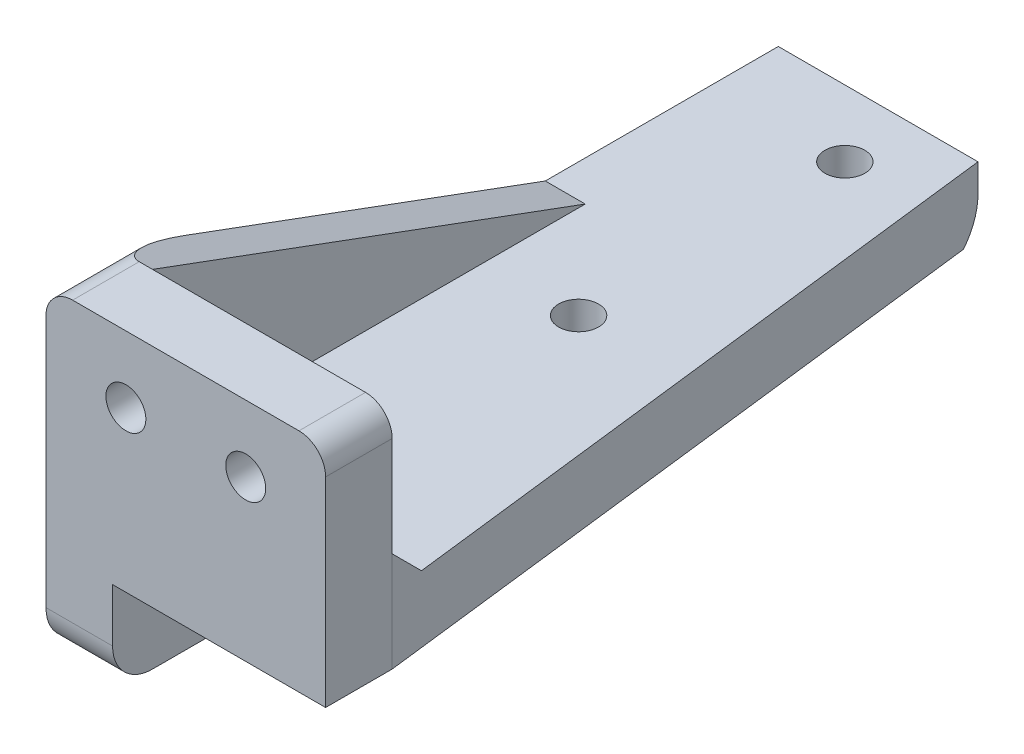
SolidWorks part; units mm, degrees
material "聚脂树脂"
ref_plane "前视基准面" through (0, 0, 0) normal (0, 0, 1) x (1, 0, 0)
ref_plane "上视基准面" through (0, 0, 0) normal (0, 1, 0) x (1, 0, 0)
ref_plane "右视基准面" through (0, 0, 0) normal (1, 0, 0) x (0, 0, -1)
other "Configuration Table"
sketch "草图1" plane through (0, 0, 0) normal (0, 1, 0) x (1, 0, 0)
  line L0 (7.5, -25) -> (13.5, -25)
  line L1 (-7.5, -25) -> (7.5, -25)
  line L2 (-7.5, -25) -> (-7.5, 25)
  line L3 (-7.5, 25) -> (7.5, 25)
  line L4 (7.5, -25) -> (7.5, 25)
  line L5 (-7.5, -25) -> (7.5, 25) construction
  line L6 (-7.5, 25) -> (7.5, -25) construction
  line L7 (13.5, -25) -> (7.5, 25)
  point P0 (0, 0)
  dimension "D1" = 15
  dimension "D2" = 6
  dimension "D3" = 50
extrude "凸台-拉伸1" add sketch "草图1" along normal blind 5 contours L1 L4 L3 L2 | L0 L7 L4
sketch "草图3" plane through (-7.5, 0, 0) normal (-1, 0, 0) x (0, 0, 1)
  line L0 (-25, 0) -> (25, 0)
  line L1 (25, 0) -> (25, -1)
  line L2 (25, -1) -> (-25, -1)
  line L3 (-25, -1) -> (-25, 0)
  line L4 (-25, -1) -> (15, -2)
  line L5 (15, -2) -> (25, -2)
  line L6 (25, -2) -> (25, -1)
  line L7 (25, -2) -> (25, -7)
  line L8 (25, -7) -> (15, -7)
  line L9 (15, -7) -> (15, -2)
  line M10 (-25, 0) -> (25, 0)
  dimension "D1" = 1
  dimension "D2" = 1
  dimension "D3" = 10
  dimension "D4" = 5
  dimension "D5" = 5
extrude "凸台-拉伸2" add sketch "草图3" against normal blind 5 contours L3 L2 L1 M10 | L5 L6 L2 L4 | L9 L8 L7 L5
fillet "圆角1" radius 4 1 edges at (-5, -1, -25)
fillet "圆角2" radius 2 1 edges at (-5, -7, 15)
sketch "草图4" plane through (0, 0, 0) normal (0, -1, 0) x (1, 0, 0)
  line L0 (-2.5, -23.7537) -> (-2.5, 25) construction
  line L1 (-2.5, -21.1) -> (-2.5, 15) construction
  line L2 (-2.5, -25) -> (7.5, -25) construction
  circle A0 centre (2.5, 20) radius 1.5
  circle A1 centre (2.5, 0) radius 1.5
  circle A2 centre (2.5, -20) radius 1.5
  dimension "D1" = 3
  dimension "D2" = 3
  dimension "D3" = 3
  dimension "D4" = 5
  dimension "D5" = 5
  dimension "D6" = 5
  dimension "D7" = 20
  dimension "D8" = 20
  dimension "D9" = 5
extrude "切除-拉伸1" cut sketch "草图4" against normal blind 5
sketch "草图5" plane through (0, 0, 25) normal (0, 0, 1) x (1, 0, 0)
  line L0 (13.5, 5) -> (13.5, 0)
  line L1 (-2.5, 0) -> (13.5, 0) construction
  line L2 (13.5, 5) -> (13.5, 0) construction
  line L3 (13.5, 0) -> (-2.5, 0)
  line L4 (-2.5, 0) -> (-2.5, -7)
  line L5 (-2.5, -7) -> (-7.5, -7)
  line L6 (-7.5, -7) -> (-7.5, 5)
  line L7 (-7.5, 5) -> (-7.5, 17)
  line L8 (-7.5, 17) -> (13.5, 17)
  line L9 (13.5, 17) -> (13.5, 5)
  circle A0 centre (-1.5, 12) radius 1.5
  circle A1 centre (7.5, 12) radius 1.5
  dimension "D2" = 3
  dimension "D3" = 3
  dimension "D1" = 12
  dimension "D4" = 5
  dimension "D5" = 6
  dimension "D6" = 6
  dimension "D7" = 5
extrude "凸台-拉伸3" add sketch "草图5" along normal blind 5
chamfer "倒角1" distance 2.5 angle 45 1 edges at (3, 5, 25)
fillet "圆角4" radius 3 1 edges at (-5, -7, 30)
sketch "草图6" plane through (-7.5, 0, 0) normal (-1, 0, 0) x (0, 0, 1)
  line L0 (25, 17) -> (25, 7.5)
  line L1 (25, 7.5) -> (22.5, 5)
  line L2 (22.5, 5) -> (-7.5, 5)
  line L3 (22.5, 5) -> (-25, 5) construction
  line L4 (-7.5, 5) -> (25, 17)
  dimension "D1" = 30
extrude "凸台-拉伸4" add sketch "草图6" against normal blind 3
fillet "圆角5" radius 2 2 edges at (13.5, 17, 27.5) (-7.5, 17, 27.5)
